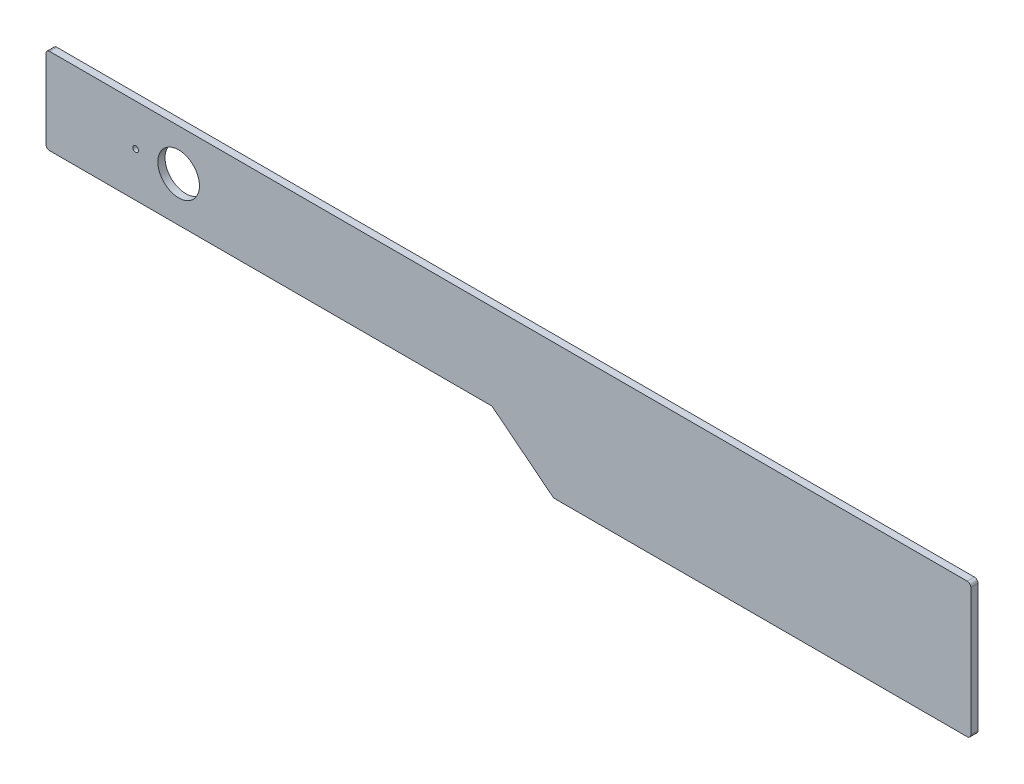
SolidWorks part; units mm, degrees
ref_plane "Спереди" through (0, 0, 0) normal (0, 0, 1) x (1, 0, 0)
ref_plane "Сверху" through (0, 0, 0) normal (0, 1, 0) x (1, 0, 0)
ref_plane "Справа" through (0, 0, 0) normal (1, 0, 0) x (0, 0, -1)
sketch "Эскиз1" plane through (0, 0, 0) normal (0, 0, 1) x (1, 0, 0)
  line L0 (6.1637, -12.6922) -> (-2.1637, -6.1078)
  line L1 (-64, 6) -> (64, 6)
  line L2 (-64.5, 5.5) -> (-64.5, -5.5)
  line L3 (-64, -6) -> (-2.4738, -6)
  line L4 (64.5, 5.5) -> (64.5, -6)
  line L5 (-64.5, 6) -> (64.5, -6) construction
  line L6 (-64.5, -6) -> (64.5, 6) construction
  line L8 (64.5, -6) -> (64.5, -12.3)
  line L9 (64, -12.8) -> (6.4738, -12.8)
  circle A0 centre (-46, 0.2) radius 2.9
  circle A1 centre (-52, 0.2) radius 0.4
  arc A2 (64, 6) -> (64.5, 5.5) centre (64, 5.5) cw
  arc A3 (64.5, -12.3) -> (64, -12.8) centre (64, -12.3) cw
  arc A4 (6.4738, -12.8) -> (6.1637, -12.6922) centre (6.4738, -12.3) cw
  arc A5 (-2.1637, -6.1078) -> (-2.4738, -6) centre (-2.4738, -6.5) ccw
  arc A6 (-64, -6) -> (-64.5, -5.5) centre (-64, -5.5) cw
  arc A7 (-64.5, 5.5) -> (-64, 6) centre (-64, 5.5) cw
  point P0 (0, 0)
  point P18 (64.5, -12.8)
  point P21 (6.3, -12.8)
  point P24 (-2.3, -6)
  dimension "D6" = 0.8
  dimension "D7" = 5.8
  dimension "D12" = 0.5
  dimension "D1" = 129
  dimension "D2" = 12
  dimension "D3" = 18.8
  dimension "D4" = 58.2
  dimension "D5" = 62.2
  dimension "D8" = 5.8
  dimension "D9" = 5.8
  dimension "D10" = 6
  dimension "D11" = 12.5
extrude "Бобышка-Вытянуть1" add sketch "Эскиз1" along normal blind 1
